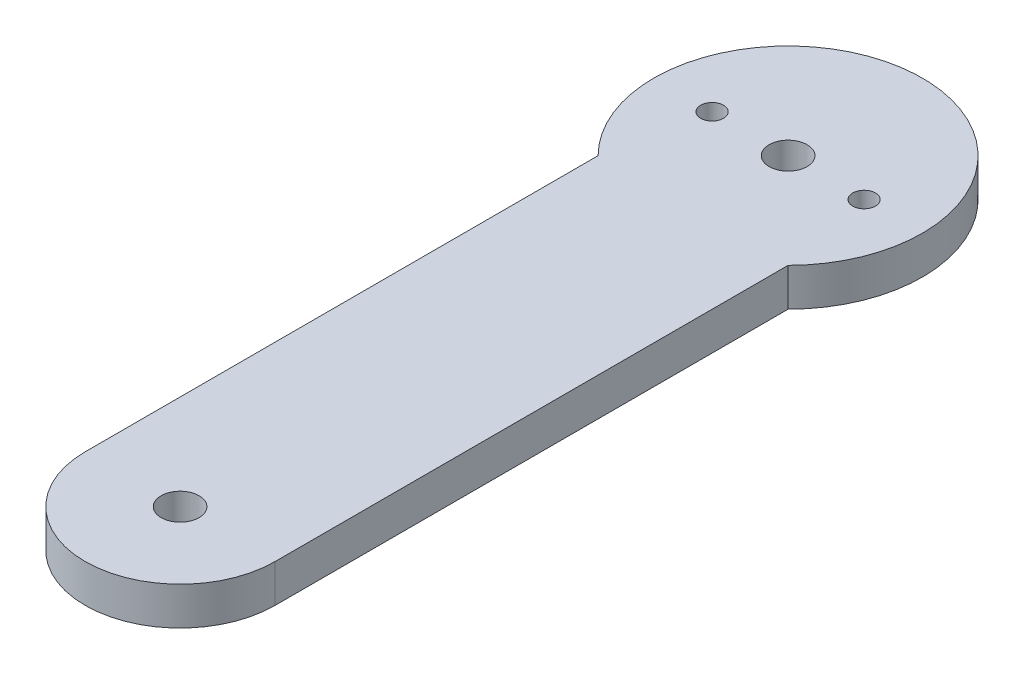
SolidWorks part; units mm, degrees
ref_plane "Front Plane" through (0, 0, 0) normal (0, 0, 1) x (1, 0, 0)
ref_plane "Top Plane" through (0, 0, 0) normal (0, 1, 0) x (1, 0, 0)
ref_plane "Right Plane" through (0, 0, 0) normal (1, 0, 0) x (0, 0, -1)
sketch "Sketch1" plane through (0, 0, 0) normal (0, 1, 0) x (1, 0, 0)
  line L0 (0, 0) -> (0, 80) construction
  line L1 (0, 80) -> (-12.5, 67.5) construction
  line L2 (-12.5, 67.5) -> (12.5, 67.5) construction
  line L3 (12.5, 67.5) -> (0, 80) construction
  line L4 (-12.5, 67.5) -> (-12.5, 0)
  line L5 (12.5, 67.5) -> (12.5, 0)
  arc A0 (12.5, 67.5) -> (-12.5, 67.5) centre (0, 80) ccw
  arc A1 (12.5, 0) -> (-12.5, 0) centre (0, 0) cw
  circle A2 centre (0, 0) radius 2.5
  circle A3 centre (0, 0) radius 20 construction
  circle A4 centre (0, 30) radius 10 construction
  circle A5 centre (0, 80) radius 2.5
  circle A6 centre (10, 80) radius 1.5
  circle A7 centre (-10, 80) radius 1.5
  point P12 (0, 10.11)
other "AlignGroup1" parameters "D2"=20.6082, "D3"=4.5368, "D4"=51.3118, "D5"=40.5744, "D6"=40, "D7"=4.104, "D10"=5, "D8"=4.0864, "D9"=5, "D1"=48.693
extrude "Boss-Extrude1" add sketch "Sketch1" along normal blind 5
